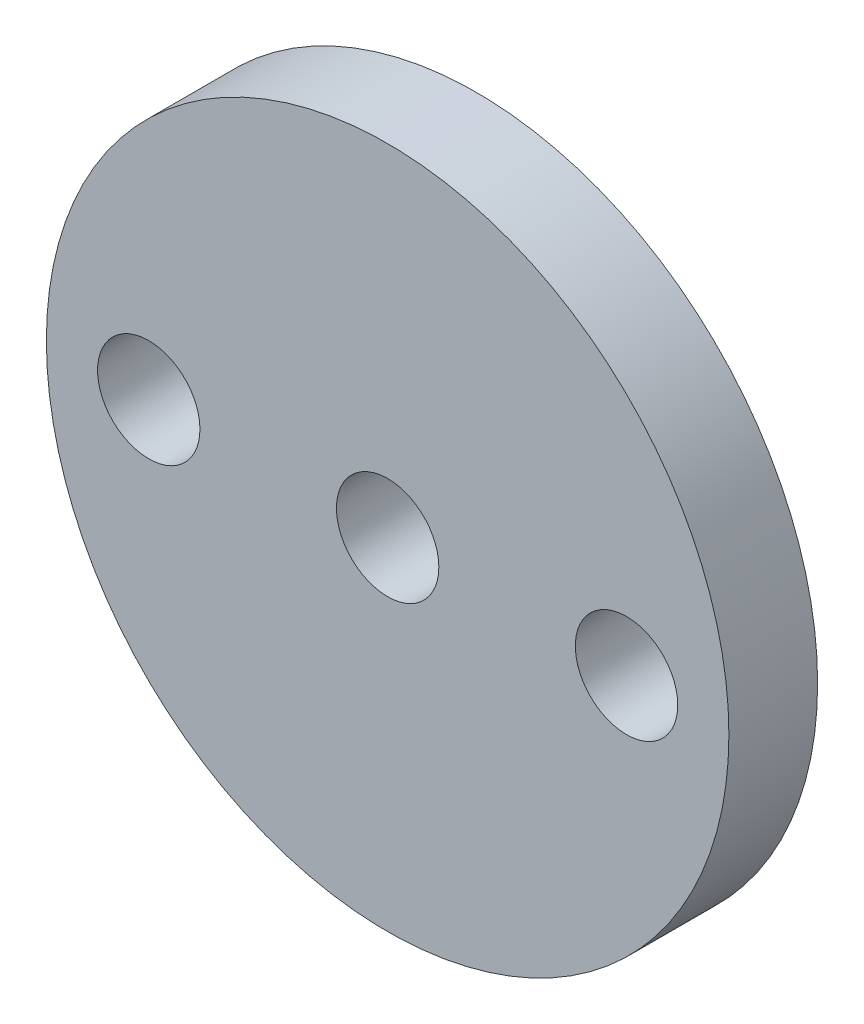
SolidWorks part; units mm, degrees
ref_plane "Front Plane" through (0, 0, 0) normal (0, 0, 1) x (1, 0, 0)
ref_plane "Top Plane" through (0, 0, 0) normal (0, 1, 0) x (1, 0, 0)
ref_plane "Right Plane" through (0, 0, 0) normal (1, 0, 0) x (0, 0, -1)
sketch "Sketch1" plane through (0, 0, 0) normal (0, 0, 1) x (1, 0, 0)
  circle A0 centre (0, 0) radius 10
  circle A1 centre (0, 0) radius 1.5
  circle A2 centre (7, 0) radius 1.5
  circle A3 centre (-7, 0) radius 1.5
  point P8 (0, 0)
  dimension "D1" = 3
  dimension "D2" = 20
  dimension "D5" = 3
  dimension "D6" = 3
  dimension "D3" = 7
  dimension "D4" = 7
extrude "Boss-Extrude1" add sketch "Sketch1" along normal blind 2.6
